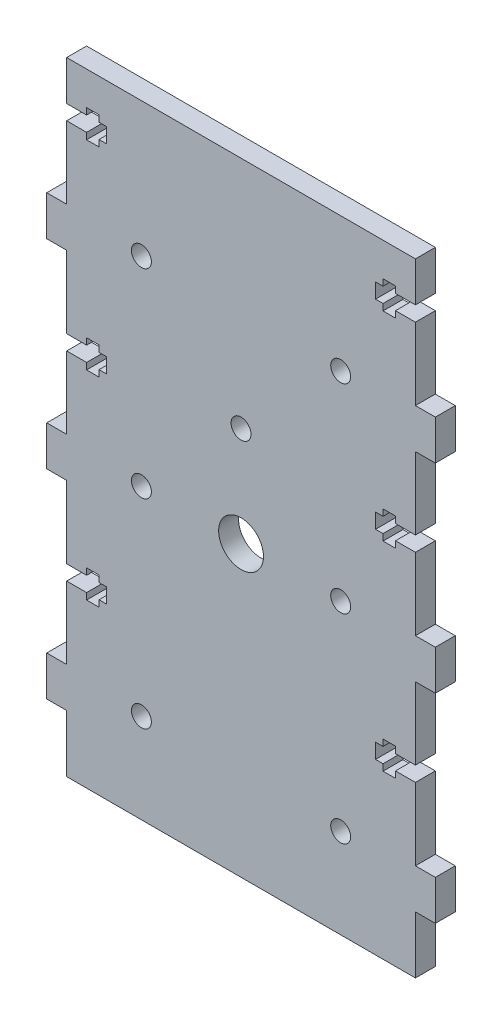
SolidWorks part; units mm, degrees
ref_plane "前视基准面" through (0, 0, 0) normal (0, 0, 1) x (1, 0, 0)
ref_plane "上视基准面" through (0, 0, 0) normal (0, 1, 0) x (1, 0, 0)
ref_plane "右视基准面" through (0, 0, 0) normal (1, 0, 0) x (0, 0, -1)
sketch "草图1" plane through (0, 0, 0) normal (0, 0, 1) x (1, 0, 0)
  line L0 (0, 3) -> (35, 3) construction
  line L1 (-35, 50) -> (35, 50)
  line L3 (-35, -87) -> (35, -87)
  line L4 (35, 50) -> (35, -87) construction
  line L5 (0, 3) -> (-35, 3) construction
  line L6 (35, -41.0024) -> (31, -41.0024)
  line L7 (31, -41.0024) -> (31, -42.3024)
  line L8 (31, -42.3024) -> (28.5, -42.3024)
  line L9 (28.5, -42.3024) -> (28.5, -41.0024)
  line L10 (28.5, -41.0024) -> (27, -41.0024)
  line L11 (27, -41.0024) -> (27, -38.0024)
  line L12 (27, -38.0024) -> (28.5, -38.0024)
  line L13 (28.5, -38.0024) -> (28.5, -36.7024)
  line L14 (28.5, -36.7024) -> (31, -36.7024)
  line L15 (31, -36.7024) -> (31, -38.0024)
  line L16 (31, -38.0024) -> (35, -38.0024)
  line L17 (35, -23.5024) -> (35, -38.0024)
  line L18 (35, -15.5024) -> (39, -15.5024)
  line L19 (39, -15.5024) -> (39, -23.5024)
  line L20 (39, -23.5024) -> (35, -23.5024)
  line L21 (39, -19.5024) -> (37.9722, -19.5024) construction
  line L22 (31, -1.0024) -> (35, -1.0024)
  line L23 (31, -2.3024) -> (31, -1.0024)
  line L24 (28.5, -2.3024) -> (31, -2.3024)
  line L25 (28.5, -1.0024) -> (28.5, -2.3024)
  line L26 (27, -1.0024) -> (28.5, -1.0024)
  line L27 (27, 1.9976) -> (27, -1.0024)
  line L28 (28.5, 1.9976) -> (27, 1.9976)
  line L29 (28.5, 3.2976) -> (28.5, 1.9976)
  line L30 (31, 3.2976) -> (28.5, 3.2976)
  line L31 (31, 1.9976) -> (31, 3.2976)
  line L32 (35, 1.9976) -> (31, 1.9976)
  line L33 (35, -1.0024) -> (35, -15.5024)
  line L34 (27, 0.4976) -> (28.5, 0.4976) construction
  line L35 (39, 24.4976) -> (35, 24.4976)
  line L36 (39, 16.4976) -> (39, 24.4976)
  line L37 (35, 16.4976) -> (39, 16.4976)
  line L38 (35, 16.4976) -> (35, 1.9976)
  line L41 (39, 20.4976) -> (36.5272, 20.4976) construction
  line L42 (27, 40.4976) -> (28.5, 40.4976) construction
  line L43 (35, 38.9976) -> (31, 38.9976)
  line L44 (31, 38.9976) -> (31, 37.6976)
  line L45 (31, 37.6976) -> (28.5, 37.6976)
  line L46 (28.5, 37.6976) -> (28.5, 38.9976)
  line L47 (28.5, 38.9976) -> (27, 38.9976)
  line L48 (27, 38.9976) -> (27, 41.9976)
  line L49 (27, 41.9976) -> (28.5, 41.9976)
  line L50 (28.5, 41.9976) -> (28.5, 43.2976)
  line L51 (28.5, 43.2976) -> (31, 43.2976)
  line L52 (31, 43.2976) -> (31, 41.9976)
  line L53 (31, 41.9976) -> (35, 41.9976)
  line L54 (35, 24.4976) -> (35, 38.9976)
  line L55 (35, 41.9976) -> (35, 50)
  line L56 (27, -39.5024) -> (31, -39.5024) construction
  line L57 (39, -59.5024) -> (37.9722, -59.5024) construction
  line L58 (39, -55.5024) -> (35, -55.5024)
  line L59 (39, -63.5024) -> (39, -55.5024)
  line L60 (35, -63.5024) -> (39, -63.5024)
  line L61 (35, -55.5024) -> (35, -41.0024)
  line L62 (35, -63.5024) -> (35, -87)
  line L63 (0, -17) -> (0, -28.0673) construction
  line L64 (-39, -59.5024) -> (-37.9722, -59.5024) construction
  line L65 (-27, -39.5024) -> (-31, -39.5024) construction
  line L66 (-27, 40.4976) -> (-28.5, 40.4976) construction
  line L67 (-39, 20.4976) -> (-36.5272, 20.4976) construction
  line L68 (-27, 0.4976) -> (-28.5, 0.4976) construction
  line L69 (-39, -19.5024) -> (-37.9722, -19.5024) construction
  line L70 (-35, 50) -> (-35, -87) construction
  line L71 (-35, -63.5024) -> (-35, -87)
  line L72 (-35, -55.5024) -> (-35, -41.0024)
  line L73 (-35, -63.5024) -> (-39, -63.5024)
  line L74 (-39, -63.5024) -> (-39, -55.5024)
  line L75 (-39, -55.5024) -> (-35, -55.5024)
  line L76 (-35, 41.9976) -> (-35, 50)
  line L77 (-35, 24.4976) -> (-35, 38.9976)
  line L78 (-31, 41.9976) -> (-35, 41.9976)
  line L79 (-31, 43.2976) -> (-31, 41.9976)
  line L80 (-28.5, 43.2976) -> (-31, 43.2976)
  line L81 (-28.5, 41.9976) -> (-28.5, 43.2976)
  line L82 (-27, 41.9976) -> (-28.5, 41.9976)
  line L83 (-27, 38.9976) -> (-27, 41.9976)
  line L84 (-28.5, 38.9976) -> (-27, 38.9976)
  line L85 (-28.5, 37.6976) -> (-28.5, 38.9976)
  line L86 (-31, 37.6976) -> (-28.5, 37.6976)
  line L87 (-31, 38.9976) -> (-31, 37.6976)
  line L88 (-35, 38.9976) -> (-31, 38.9976)
  line L89 (-35, 16.4976) -> (-35, 1.9976)
  line L90 (-35, 16.4976) -> (-39, 16.4976)
  line L91 (-39, 16.4976) -> (-39, 24.4976)
  line L92 (-39, 24.4976) -> (-35, 24.4976)
  line L93 (-35, -1.0024) -> (-35, -15.5024)
  line L94 (-35, 1.9976) -> (-31, 1.9976)
  line L95 (-31, 1.9976) -> (-31, 3.2976)
  line L96 (-31, 3.2976) -> (-28.5, 3.2976)
  line L97 (-28.5, 3.2976) -> (-28.5, 1.9976)
  line L98 (-28.5, 1.9976) -> (-27, 1.9976)
  line L99 (-27, 1.9976) -> (-27, -1.0024)
  line L100 (-27, -1.0024) -> (-28.5, -1.0024)
  line L101 (-28.5, -1.0024) -> (-28.5, -2.3024)
  line L102 (-28.5, -2.3024) -> (-31, -2.3024)
  line L103 (-31, -2.3024) -> (-31, -1.0024)
  line L104 (-31, -1.0024) -> (-35, -1.0024)
  line L105 (-39, -23.5024) -> (-35, -23.5024)
  line L106 (-39, -15.5024) -> (-39, -23.5024)
  line L107 (-35, -15.5024) -> (-39, -15.5024)
  line L108 (-35, -23.5024) -> (-35, -38.0024)
  line L109 (-31, -38.0024) -> (-35, -38.0024)
  line L110 (-31, -36.7024) -> (-31, -38.0024)
  line L111 (-28.5, -36.7024) -> (-31, -36.7024)
  line L112 (-28.5, -38.0024) -> (-28.5, -36.7024)
  line L113 (-27, -38.0024) -> (-28.5, -38.0024)
  line L114 (-27, -41.0024) -> (-27, -38.0024)
  line L115 (-28.5, -41.0024) -> (-27, -41.0024)
  line L116 (-28.5, -42.3024) -> (-28.5, -41.0024)
  line L117 (-31, -42.3024) -> (-28.5, -42.3024)
  line L118 (-31, -41.0024) -> (-31, -42.3024)
  line L119 (-35, -41.0024) -> (-31, -41.0024)
  line L120 (-20, -17) -> (-20, -57) construction
  circle A0 centre (0, -17) radius 4.5
  circle A2 centre (20, -17) radius 2
  circle A3 centre (0, 3) radius 2
  circle A9 centre (-20, 23) radius 2
  circle A10 centre (20, 23) radius 2
  circle A11 centre (-20, -17) radius 2
  circle A12 centre (-20, -57) radius 2
  circle A13 centre (20, -57) radius 2
  point P30 (29.75, -36.7024)
  dimension "D1" = 9
  dimension "D4" = 4
  dimension "D9" = 40
  dimension "D10" = 40
  dimension "D2" = 20
  dimension "D3" = 20
  dimension "D6" = 35
  dimension "D8" = 70
  dimension "D5" = 40
  dimension "D11" = 40
  dimension "D12" = 4
  dimension "D13" = 2.5
  dimension "D14" = 1.5
  dimension "D15" = 3
  dimension "D16" = 5.6
  dimension "D17" = 18.5
  dimension "D18" = 8
  dimension "D19" = 4
extrude "凸台-拉伸1" add sketch "草图1" along normal blind 4 contours L3 L6 L7 L8 L9 L10 L11 L12 L13 L14 L15 L16 L17 L20 L19 L18 L33 L22 L23 L24 L25 L26 L27 L28 L29 L30 L31 L32 L38 L37 L36 L35 L1
sketch "草图2" plane through (-35, 0, 0) normal (-1, 0, 0) x (0, 0, 1)
  line L0 (2, 1.9976) -> (2, -1.0024)
  line L1 (4, 1.9976) -> (0, 1.9976) construction
  line L2 (4, -1.0024) -> (0, -1.0024) construction
  circle A0 centre (2, 0.4976) radius 1.5
sketch "草图3" plane through (35, 0, 0) normal (1, 0, 0) x (0, 0, -1)
  line L0 (-2, 1.9976) -> (-2, -1.0024)
  line L1 (-4, 1.9976) -> (0, 1.9976) construction
  line L2 (-4, -1.0024) -> (0, -1.0024) construction
  circle A0 centre (-2, 0.4976) radius 1.5
sketch "草图4" plane through (0, 0, 4) normal (0, 0, 1) x (1, 0, 0)
  line L0 (-35, -63.5024) -> (-35, -87) construction
  line L1 (35, -87) -> (-35, -87)
  line L2 (35, -87) -> (35, -75)
  line L3 (35, -75) -> (-35, -75)
  line L4 (-35, -87) -> (-35, -75)
  dimension "D1" = 12
extrude "切除-拉伸1" cut sketch "草图4" against normal blind 4 contours L3 L4 L1 L2
